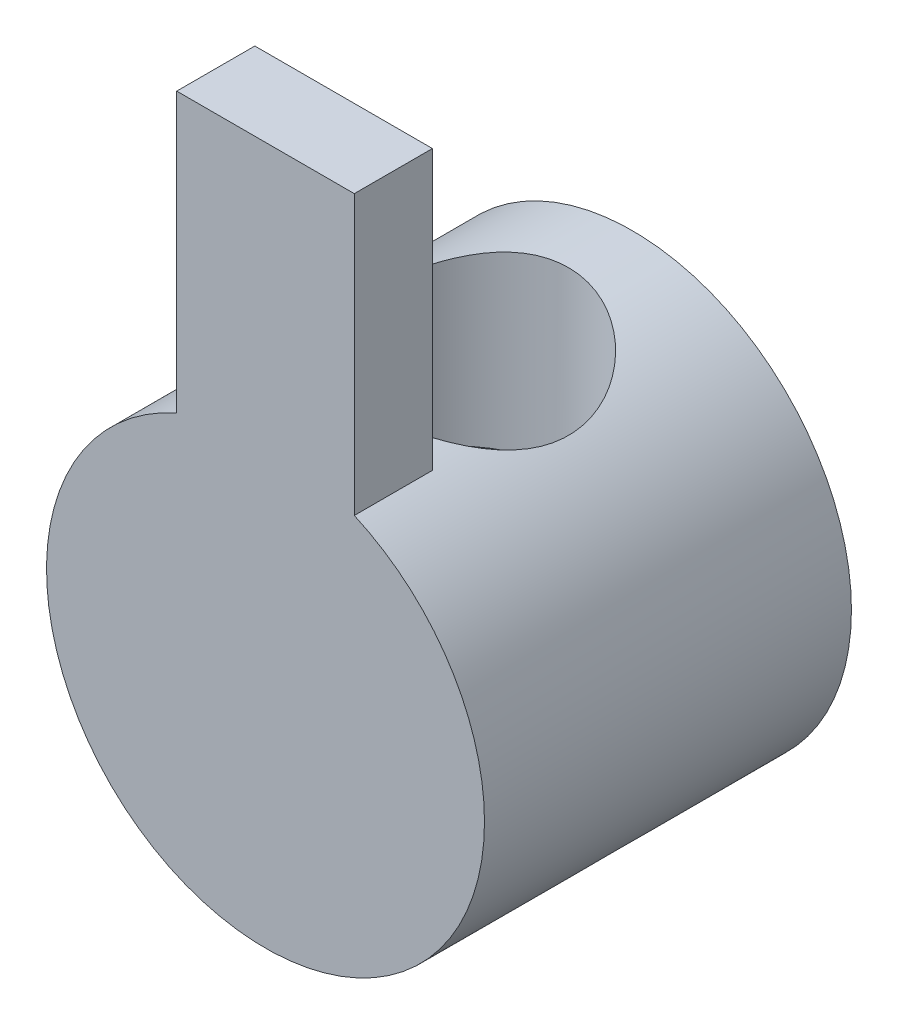
SolidWorks part; units mm, degrees
ref_plane "前视基准面" through (0, 0, 0) normal (0, 0, 1) x (1, 0, 0)
ref_plane "上视基准面" through (0, 0, 0) normal (0, 1, 0) x (1, 0, 0)
ref_plane "右视基准面" through (0, 0, 0) normal (1, 0, 0) x (0, 0, -1)
sketch "草图1" plane through (0, 0, 0) normal (0, 0, 1) x (1, 0, 0)
  line L1 (-3.75, -15.25) -> (3.75, -15.25)
  line L2 (-3.75, -15.25) -> (-3.75, 15.25)
  line L3 (-3.75, 15.25) -> (3.75, 15.25)
  line L4 (3.75, -15.25) -> (3.75, 15.25)
  line L5 (-3.75, -15.25) -> (3.75, 15.25) construction
  line L6 (-3.75, 15.25) -> (3.75, -15.25) construction
  point P0 (0, 0)
  dimension "D1" = 7.5
  dimension "D2" = 30.5
extrude "凸台-拉伸1" add sketch "草图1" along normal blind 3.3
sketch "草图4" plane through (0, 0, 0) normal (0, 0, -1) x (-1, 0, 0)
  line L0 (3.75, 15.25) -> (3.75, -15.25) construction
  line L1 (-3.75, -15.25) -> (3.75, -15.25)
  line L2 (-3.75, -15.25) -> (-3.75, -7.0516)
  line L3 (-3.75, -7.0516) -> (3.75, -7.0516)
  line L4 (3.75, -15.25) -> (3.75, -7.0516)
extrude "切除-拉伸1" cut sketch "草图4" against normal through all
sketch "草图2" plane through (0, 0, 3.3) normal (0, 0, 1) x (1, 0, 0)
  circle A0 centre (0, -4.98) radius 9.25
  dimension "D1" = 18.5
extrude "凸台-拉伸2" add sketch "草图2" against normal blind 15.5
sketch "草图5" plane through (0, 15.25, 0) normal (0, 1, 0) x (1, 0, 0)
  line L0 (0, -3.3) -> (0, 12.2) construction
  line L1 (3.75, -3.3) -> (-3.75, -3.3) construction
  line L2 (9.25, 12.2) -> (-9.25, 12.2) construction
  circle A0 centre (0, 4.7) radius 4.8
  dimension "D1" = 9.6
  dimension "D2" = 8
extrude "切除-拉伸2" cut sketch "草图5" against normal through all
ref_plane "基准面1" through (0, -14.23, 0) normal (0, 1, 0) x (-1, 0, 0)
ref_plane "基准面2" through (0, -6, 0) normal (0, 1, 0) x (1, 0, 0)
sketch "草图6" plane through (0, -6, 0) normal (0, 1, 0) x (1, 0, 0)
  circle A0 centre (0, 4.7) radius 6.75
extrude "切除-拉伸3" cut sketch "草图6" against normal blind 10 and the other way blind 2.75
sketch "草图7" plane through (0, 0, 0) normal (0, 0, -1) x (-1, 0, 0)
  line L0 (-0.9747, 15.25) -> (-0.9747, 4.2185)
  line L1 (0.9747, 15.25) -> (0.9747, 4.2185)
  line L2 (0.9747, 4.2185) -> (0.9747, 15.25) construction
  line L3 (-0.9747, 15.25) -> (0.9747, 15.25)
  arc A0 (0.9747, 4.2185) -> (-0.9747, 4.2185) centre (0, -4.98) ccw
extrude "凸台-拉伸3" add sketch "草图7" against normal blind 0.5
